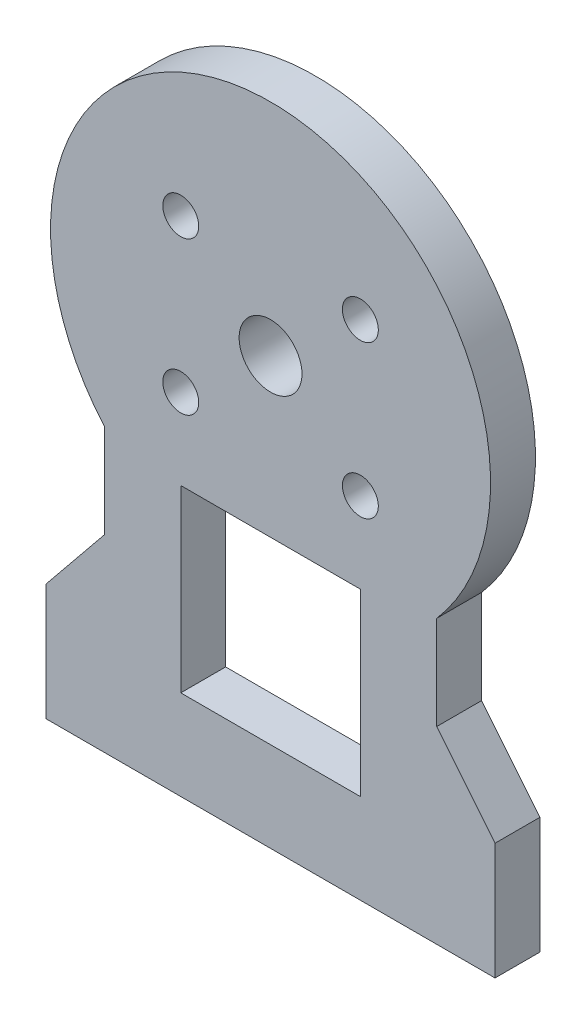
SolidWorks part; units mm, degrees
ref_plane "Płaszczyzna przednia" through (0, 0, 0) normal (0, 0, 1) x (1, 0, 0)
ref_plane "Płaszczyzna górna" through (0, 0, 0) normal (0, 1, 0) x (1, 0, 0)
ref_plane "Płaszczyzna prawa" through (0, 0, 0) normal (1, 0, 0) x (0, 0, -1)
sketch "Szkic1" plane through (0, 0, 0) normal (0, 0, 1) x (1, 0, 0)
  line L0 (0, 0) -> (0, 36) construction
  line L1 (12.5, 0) -> (-12.5, 0)
  line L2 (-12.5, 0) -> (-12.5, 6.5)
  line L3 (-9.25, 15.7188) -> (-9.25, 10.5)
  line L4 (5, 5) -> (-5, 5)
  line L5 (-5, 5) -> (-5, 15)
  line L6 (-5, 15) -> (5, 15)
  line L7 (-12.5, 6.5) -> (-9.25, 10.5)
  line L8 (12.5, 6.5) -> (9.25, 10.5)
  line L9 (5, 5) -> (5, 15)
  line L10 (9.25, 15.7188) -> (9.25, 10.5)
  line L11 (12.5, 0) -> (12.5, 6.5)
  line L12 (0, 23.75) -> (-21.0836, 23.75) construction
  arc A0 (9.25, 15.7188) -> (-9.25, 15.7188) centre (0, 23.75) ccw
  circle A1 centre (0, 23.75) radius 1.75
  circle A2 centre (-5, 28) radius 1
  circle A3 centre (-5, 19.5) radius 1
  circle A4 centre (5, 19.5) radius 1
  circle A5 centre (5, 28) radius 1
  point P16 (0, 15)
  point P17 (0, 5)
  dimension "D2" = 9.25
  dimension "D10" = 24.5
  dimension "D3" = 2
  dimension "D11" = 4.25
  dimension "D4" = 5
  dimension "D5" = 5
  dimension "D6" = 10
  dimension "D7" = 6.5
  dimension "D8" = 12.5
  dimension "D9" = 4
extrude "Dodanie-wyciągnięcie1" add sketch "Szkic1" along normal blind 2.5
